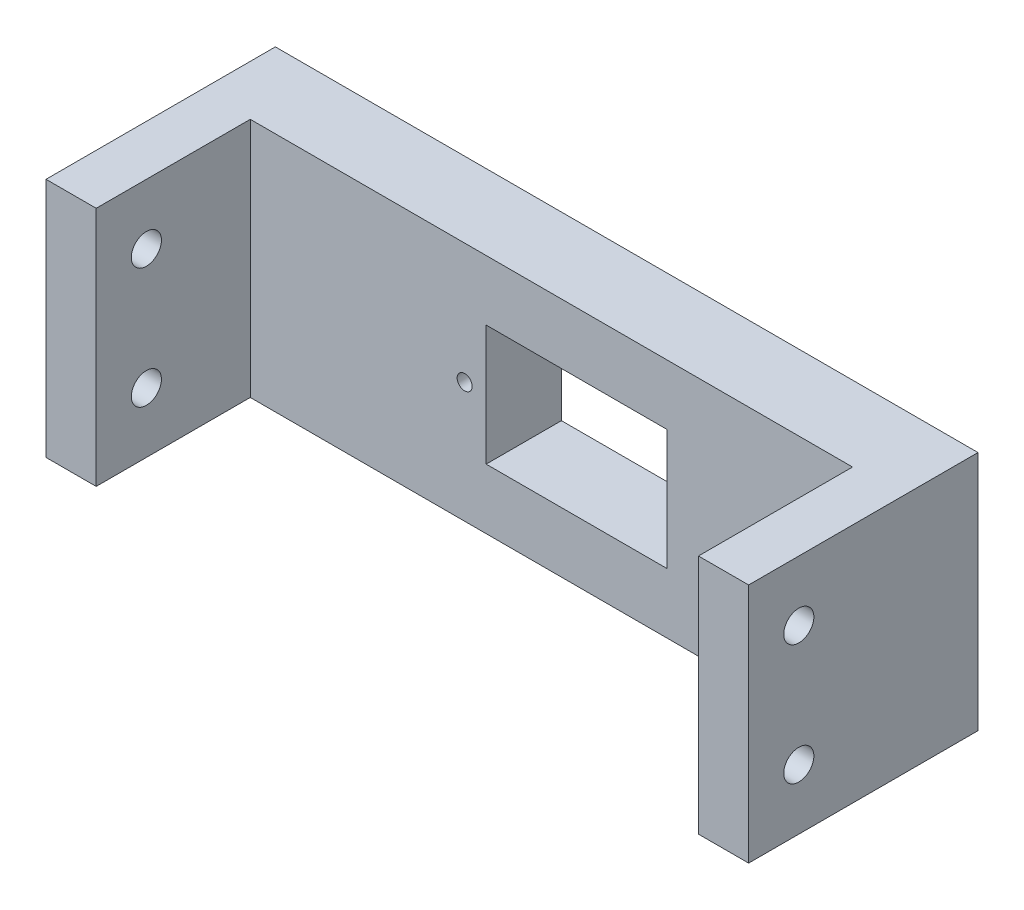
SolidWorks part; units mm, degrees
ref_plane "Front Plane" through (0, 0, 0) normal (0, 0, 1) x (1, 0, 0)
ref_plane "Top Plane" through (0, 0, 0) normal (0, 1, 0) x (1, 0, 0)
ref_plane "Right Plane" through (0, 0, 0) normal (1, 0, 0) x (0, 0, -1)
sketch "Sketch1" plane through (0, 0, 0) normal (0, 1, 0) x (1, 0, 0)
  line L0 (-30, -3.75) -> (-30, -19.1)
  line L1 (-35, 3.75) -> (35, 3.75)
  line L2 (0, 3.75) -> (0, -3.75) construction
  line L3 (-35, -3.75) -> (35, -3.75)
  line L4 (35, 3.75) -> (35, -3.75)
  line L5 (35, -3.75) -> (30, -3.75)
  line L6 (35, -3.75) -> (35, -19.1)
  line L7 (35, -19.1) -> (30, -19.1)
  line L8 (30, -3.75) -> (30, -19.1)
  line L9 (-35, -19.1) -> (-30, -19.1)
  line L10 (-35, -3.75) -> (-35, -19.1)
  line L11 (-35, -3.75) -> (-30, -3.75)
  line L12 (-35, 3.75) -> (-35, -3.75)
  point P7 (0, 0)
  dimension "D1" = 35
  dimension "D2" = 22.85
  dimension "D3" = 7.5
  dimension "D4" = 5
extrude "Boss-Extrude1" add sketch "Sketch1" along normal blind 24 contours L3 L10 L9 L0 | L2 L1 L12 L3 | L1 L2 L3 L4 | L3 L8 L7 L6
sketch "Sketch2" plane through (-35, 0, 0) normal (-1, 0, 0) x (0, 0, 1)
  line L0 (-3.75, 24) -> (19.1, 24) construction
  line L1 (19.1, 24) -> (19.1, 0) construction
  circle A0 centre (14.1, 18) radius 1.5
  circle A1 centre (14.1, 6) radius 1.5
  point P9 (0, 0)
  dimension "D2" = 3
  dimension "D3" = 12
  dimension "D1" = 5
  dimension "D4" = 6
extrude "Cut-Extrude1" cut sketch "Sketch2" against normal through all
sketch "Sketch8" plane through (0, 0, -3.75) normal (0, 0, -1) x (-1, 0, 0)
  line L0 (0, 12) -> (35, 12) construction
  line L1 (35, 24) -> (35, 0) construction
  line L2 (0, 12) -> (0, 24) construction
  line L3 (35, 24) -> (-35, 24) construction
  line L5 (6.5, 18) -> (-11.5, 18)
  line L6 (6.5, 18) -> (6.5, 6)
  line L7 (6.5, 6) -> (-11.5, 6)
  line L8 (-11.5, 18) -> (-11.5, 6)
  point P0 (0, 12)
  point P12 (6.5, 12)
  dimension "D1" = 6.5
  dimension "D2" = 18
  dimension "D3" = 12
extrude "Cut-Extrude4" cut sketch "Sketch8" against normal up to next
sketch "Sketch9" plane through (0, 0, -3.75) normal (0, 0, -1) x (-1, 0, 0)
  line L0 (-35, 24) -> (-35, 0) construction
  line L1 (-19.16, 12) -> (-35, 12) construction
  circle A0 centre (-19.16, 12) radius 0.75
  circle A1 centre (8.64, 12) radius 0.75
  dimension "D3" = 1.5
  dimension "D1" = 27.8
  dimension "D2" = 15.84
extrude "Cut-Extrude5" cut sketch "Sketch9" against normal through all
